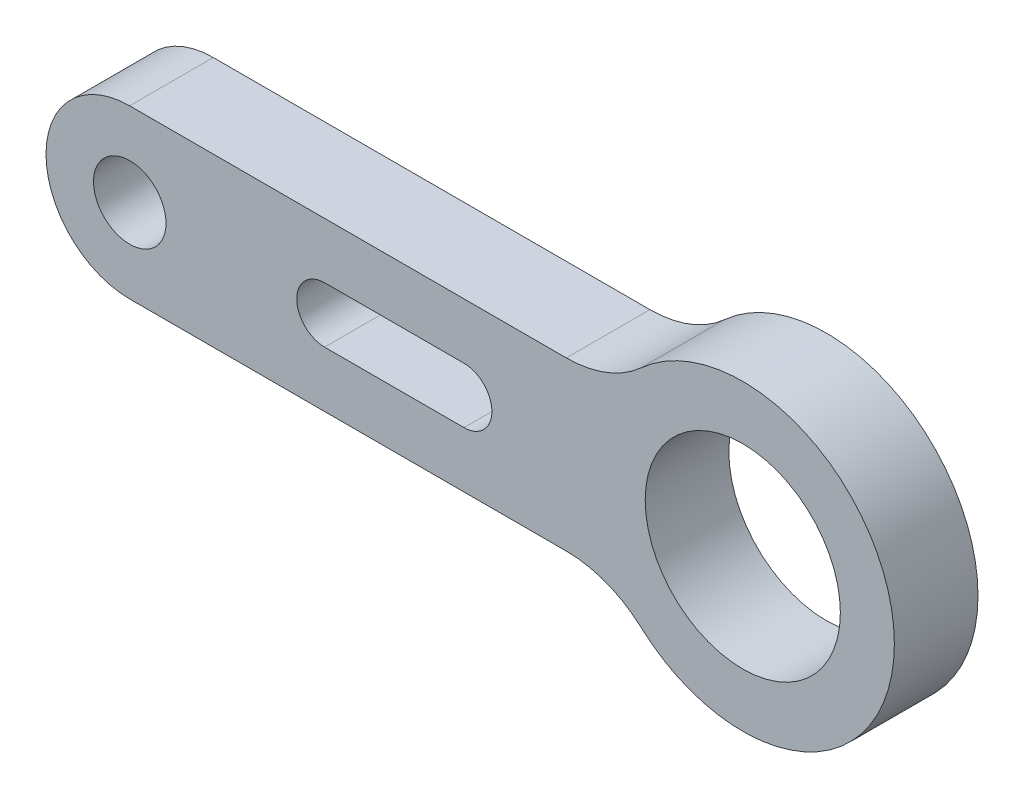
SolidWorks part; units mm, degrees
ref_plane "前视基准面" through (0, 0, 0) normal (0, 0, 1) x (1, 0, 0)
ref_plane "上视基准面" through (0, 0, 0) normal (0, 1, 0) x (1, 0, 0)
ref_plane "右视基准面" through (0, 0, 0) normal (1, 0, 0) x (0, 0, -1)
ref_plane "基准面4" through (0, 0, 0) normal (0, 0, -1) x (-1, 0, 0)
sketch "草图1" plane through (0, 0, 0) normal (0, 0, -1) x (-1, 0, 0)
  line L0 (-8.874, 2.9074) -> (-13.874, 2.9074)
  line L1 (-13.874, 4.9074) -> (-8.874, 4.9074)
  line L2 (-17.5441, 0.9071) -> (-1.8798, 0.9071)
  line L3 (-1.8798, 6.9071) -> (-17.5428, 6.9071)
  circle A0 centre (-1.884, 3.9071) radius 1.3
  arc A1 (-8.874, 4.9074) -> (-8.874, 2.9074) centre (-8.874, 3.9074) cw
  arc A2 (-13.874, 2.9074) -> (-13.874, 4.9074) centre (-13.874, 3.9074) cw
  arc A3 (-17.5428, 6.9071) -> (-20.2258, 7.9404) centre (-17.5428, 10.9071) cw
  arc A4 (-20.2258, 7.9404) -> (-20.2266, -0.1257) centre (-23.873, 3.9077) ccw
  arc A5 (-20.2266, -0.1257) -> (-17.5441, 0.9071) centre (-17.5441, -3.0929) cw
  arc A6 (-1.8798, 0.9071) -> (-1.8798, 6.9071) centre (-1.8798, 3.9071) ccw
  circle A7 centre (-23.873, 3.9077) radius 3.5
extrude "凸台-拉伸1" add sketch "草图1" against normal blind 3
